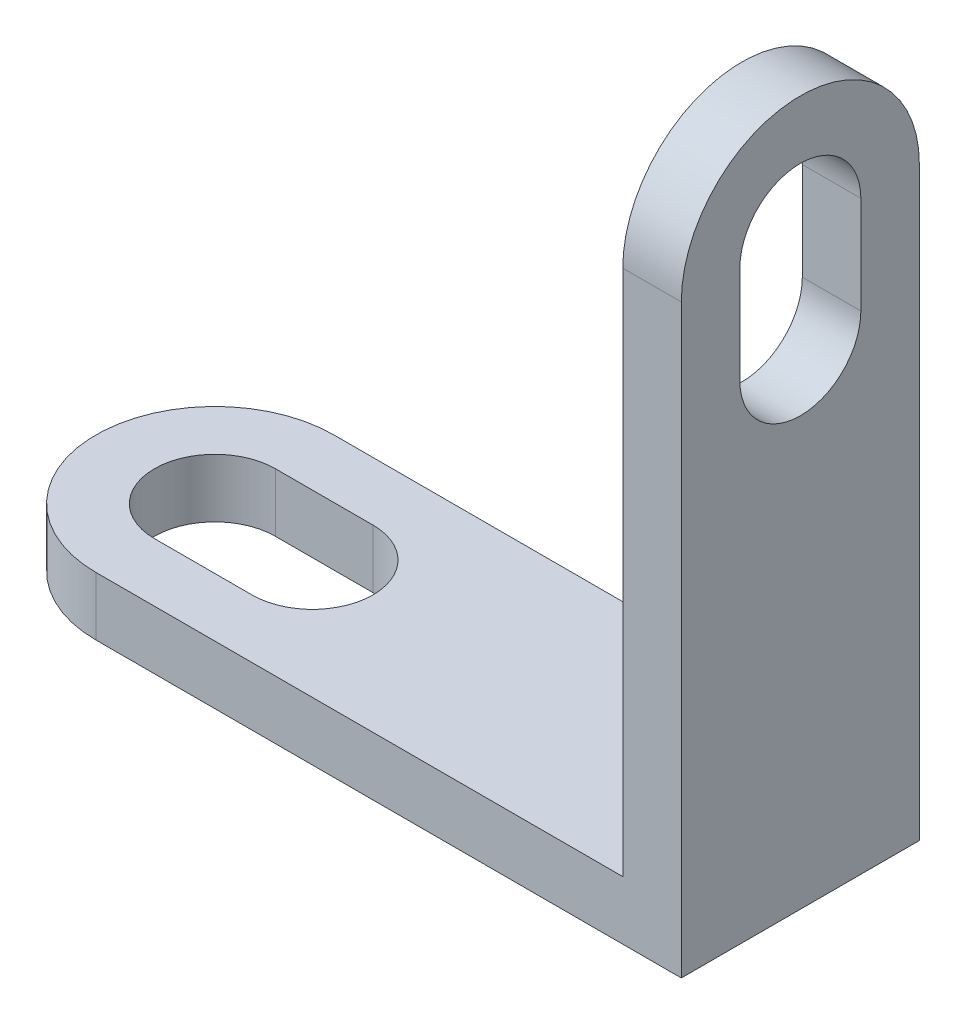
SolidWorks part; units mm, degrees
ref_plane "Front Plane" through (0, 0, 0) normal (0, 0, 1) x (1, 0, 0)
ref_plane "Top Plane" through (0, 0, 0) normal (0, 1, 0) x (1, 0, 0)
ref_plane "Right Plane" through (0, 0, 0) normal (1, 0, 0) x (0, 0, -1)
sketch "Sketch1" plane through (0, 0, 0) normal (0, 1, 0) x (1, 0, 0)
  line L0 (0, 0) -> (-30, 0) construction
  line L1 (0, -6.1) -> (-30, -6.1)
  line L2 (0, 6.1) -> (-30, 6.1)
  line L3 (-30, 0) -> (-25, 0) construction
  line L4 (-30, 3.1) -> (-25, 3.1)
  line L5 (-30, -3.1) -> (-25, -3.1)
  line L6 (0, 6.1) -> (0, -6.1)
  arc A1 (-30, 6.1) -> (-30, -6.1) centre (-30, 0) ccw
  arc A2 (-30, 3.1) -> (-30, -3.1) centre (-30, 0) ccw
  arc A3 (-25, -3.1) -> (-25, 3.1) centre (-25, 0) ccw
  point P3 (-15, 0)
  point P10 (-27.5, 0)
  dimension "D2" = 3.1
  dimension "D4" = 3
  dimension "D1" = 30
  dimension "D3" = 5
extrude "Boss-Extrude1" add sketch "Sketch1" along normal blind 3
sketch "Sketch4" plane through (0, 0, 0) normal (1, 0, 0) x (0, 0, -1)
  line L0 (0, 0) -> (0, 30) construction
  line L1 (-6.1, 0) -> (6.1, 0) construction
  line L2 (-6.1, 0) -> (-6.1, 30)
  line L3 (6.1, 0) -> (6.1, 30)
  line L4 (-6.1, 0) -> (6.1, 0)
  line L5 (0, 30) -> (0, 25) construction
  line L6 (3.1, 30) -> (3.1, 25)
  line L7 (-3.1, 30) -> (-3.1, 25)
  arc A1 (6.1, 30) -> (-6.1, 30) centre (0, 30) ccw
  arc A2 (3.1, 30) -> (-3.1, 30) centre (0, 30) ccw
  arc A3 (-3.1, 25) -> (3.1, 25) centre (0, 25) ccw
  point P4 (0, 15)
  point P9 (0, 27.5)
  dimension "D3" = 3.1
  dimension "D1" = 30
  dimension "D2" = 5
extrude "Boss-Extrude3" add sketch "Sketch4" against normal blind 3
